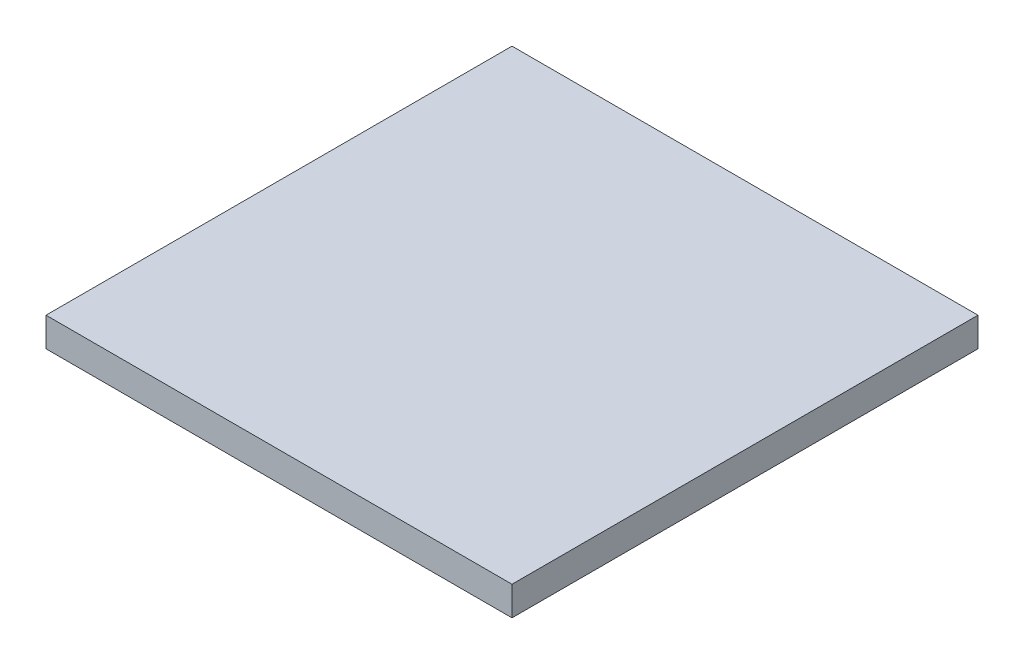
SolidWorks part; units mm, degrees
ref_plane "Front Plane" through (0, 0, 0) normal (0, 0, 1) x (1, 0, 0)
ref_plane "Top Plane" through (0, 0, 0) normal (0, 1, 0) x (1, 0, 0)
ref_plane "Right Plane" through (0, 0, 0) normal (1, 0, 0) x (0, 0, -1)
sketch "Sketch1" plane through (0, 0, 0) normal (0, 1, 0) x (1, 0, 0)
  line L1 (-304.8, 304.8) -> (304.8, 304.8)
  line L2 (-304.8, 304.8) -> (-304.8, -304.8)
  line L3 (-304.8, -304.8) -> (304.8, -304.8)
  line L4 (304.8, 304.8) -> (304.8, -304.8)
  line L5 (-304.8, 304.8) -> (304.8, -304.8) construction
  line L6 (-304.8, -304.8) -> (304.8, 304.8) construction
  point P0 (0, 0)
  dimension "D1" = 609.6
  dimension "D2" = 609.6
extrude "Boss-Extrude1" add sketch "Sketch1" along normal blind 38.1
